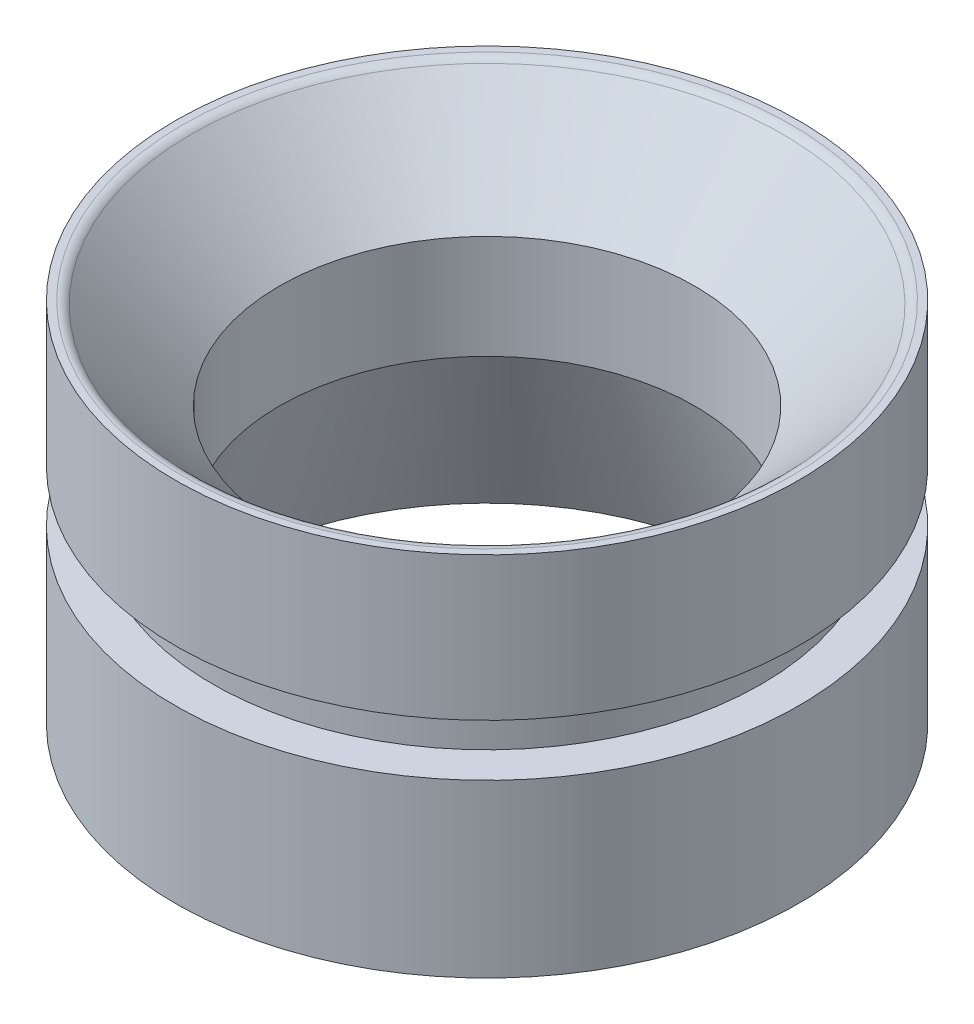
SolidWorks part; units mm, degrees
material "Copper"
ref_plane "Front Plane" through (0, 0, 0) normal (0, 0, 1) x (1, 0, 0)
ref_plane "Top Plane" through (0, 0, 0) normal (0, 1, 0) x (1, 0, 0)
ref_plane "Right Plane" through (0, 0, 0) normal (1, 0, 0) x (0, 0, -1)
sketch "Sketch1" plane through (0, 0, 0) normal (0, 0, 1) x (1, 0, 0)
  line L0 (0, 44.7791) -> (0, -23.856) construction
  line L1 (12.7, -3.175) -> (12.7, 3.175)
  line L2 (12.7, 3.175) -> (18.288, 8.763)
  line L3 (18.288, 8.763) -> (19.05, 8.763)
  line L4 (19.05, 8.763) -> (19.05, 0)
  line L5 (19.05, -13.6429) -> (16.51, -13.6429)
  line L6 (16.51, -13.6429) -> (12.7, -3.175)
  line L7 (19.05, -3.175) -> (19.05, -13.6429)
  line L8 (19.05, 0) -> (16.764, 0)
  line L10 (19.05, -3.175) -> (16.764, -3.175)
  line L12 (16.764, 0) -> (16.764, -3.175)
  point P11 (12.7, 0)
  dimension "D1" = 25.4
  dimension "D2" = 6.35
  dimension "D3" = 45
  dimension "D4" = 20
  dimension "D5" = 0.762
  dimension "D6" = 2.54
  dimension "D7" = 38.1
  dimension "D8" = 3.175
  dimension "D9" = 2.286
revolve "Revolve1" add sketch "Sketch1" angle 360 about L0
fillet "Fillet2" [suppressed] radius 1.524
fillet "Fillet3" radius 0.762 1 edges at (-18.288, 8.763, 0)
